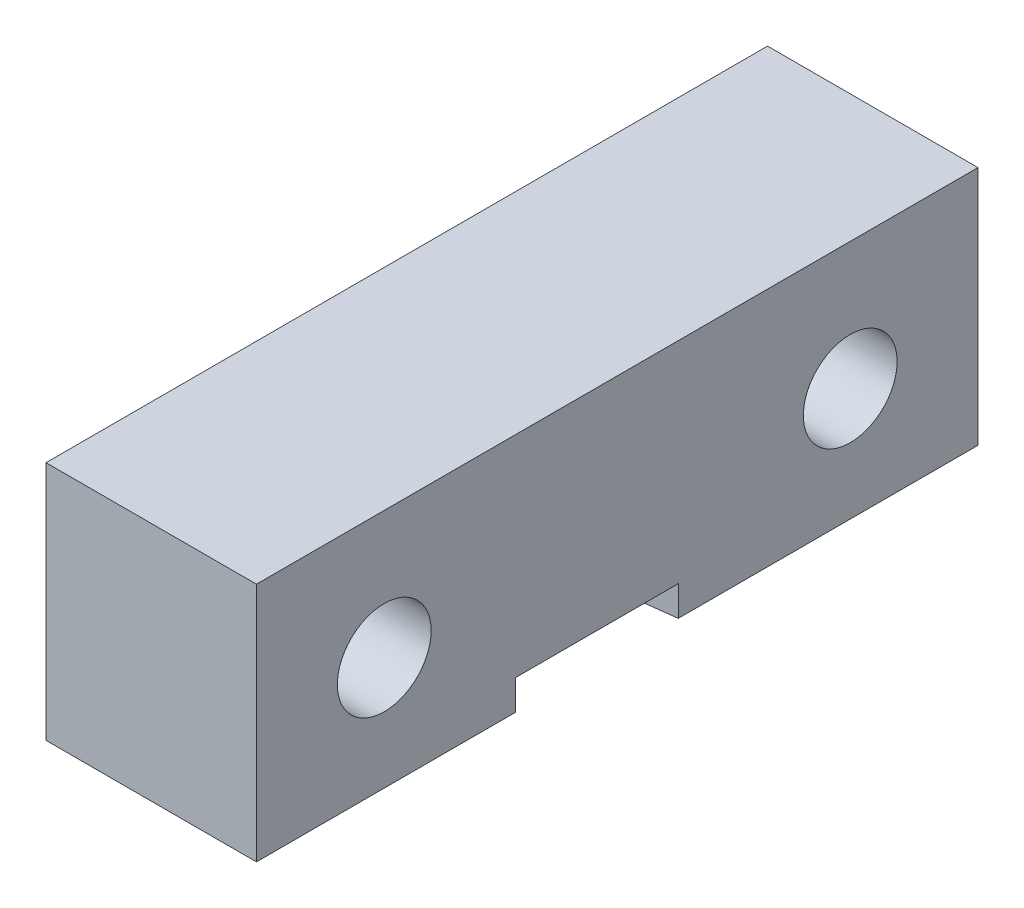
SolidWorks part; units mm, degrees
ref_plane "Front Plane" through (0, 0, 0) normal (0, 0, 1) x (1, 0, 0)
ref_plane "Top Plane" through (0, 0, 0) normal (0, 1, 0) x (1, 0, 0)
ref_plane "Right Plane" through (0, 0, 0) normal (1, 0, 0) x (0, 0, -1)
sketch "Sketch1" plane through (0, 0, 0) normal (0, 0, 1) x (1, 0, 0)
  line L1 (22.225, -25.4) -> (-22.225, -25.4)
  line L2 (22.225, -25.4) -> (22.225, 25.4)
  line L3 (22.225, 25.4) -> (-22.225, 25.4)
  line L4 (-22.225, -25.4) -> (-22.225, 25.4)
  line L5 (22.225, -25.4) -> (-22.225, 25.4) construction
  line L6 (22.225, 25.4) -> (-22.225, -25.4) construction
  point P0 (0, 0)
  dimension "D1" = 44.45
  dimension "D2" = 50.8
extrude "Boss-Extrude1" add sketch "Sketch1" along normal mid plane 152.4
sketch "Sketch2" plane through (22.225, 0, 0) normal (1, 0, 0) x (0, 0, -1)
  line L0 (-76.2, -25.4) -> (76.2, -25.4) construction
  circle A0 centre (-49.2125, -1.524) radius 6.731
  circle A1 centre (49.2125, -1.524) radius 6.731
  dimension "D4" = 13.462
  dimension "D1" = 98.425
  dimension "D2" = 49.2125
  dimension "D3" = 23.876
extrude "Cut-Extrude1" cut sketch "Sketch2" against normal up to next
sketch "Sketch3" plane through (22.225, 0, 0) normal (1, 0, 0) x (0, 0, -1)
  circle A0 centre (-49.2125, -1.524) radius 9.906
  circle A1 centre (49.2125, -1.524) radius 9.906
  dimension "D1" = 19.812
extrude "Cut-Extrude2" cut sketch "Sketch3" against normal blind 38.608
sketch "Sketch4" plane through (0, -25.4, 0) normal (0, -1, 0) x (1, 0, 0)
  line L4 (22.225, -12.8902) -> (22.225, 21.5318)
  line L5 (22.225, 76.2) -> (22.225, -76.2) construction
  line L6 (22.225, -12.8902) -> (0.9472, -10.2486)
  line L7 (22.225, 21.5318) -> (0.9472, 18.8901)
  circle A1 centre (2.756, 4.3208) radius 14.6812 construction
  arc A4 (0.9472, 18.8901) -> (0.9472, -10.2486) centre (2.756, 4.3208) ccw
extrude "Cut-Extrude3" cut sketch "Sketch4" against normal blind 6.35
